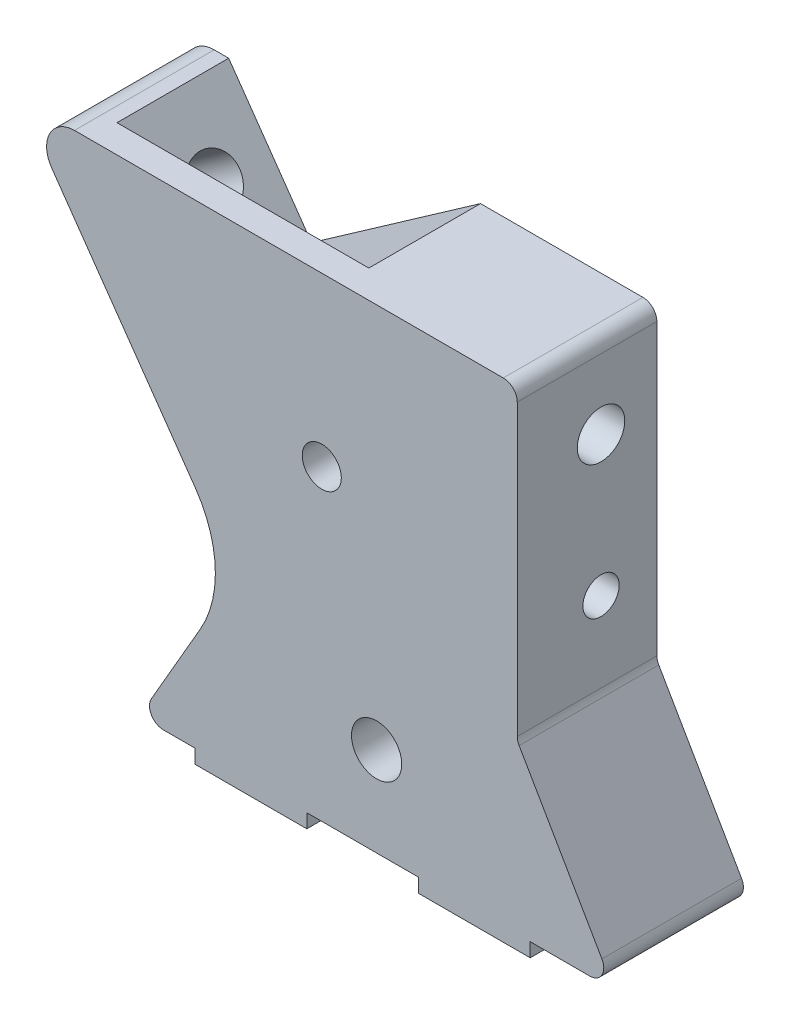
SolidWorks part; units mm, degrees
material "ABS"
ref_plane "Спереди" through (0, 0, 0) normal (0, 0, 1) x (1, 0, 0)
ref_plane "Сверху" through (0, 0, 0) normal (0, 1, 0) x (1, 0, 0)
ref_plane "Справа" through (0, 0, 0) normal (1, 0, 0) x (0, 0, -1)
sketch "Sketch1" plane through (0, 0, 0) normal (0, 0, 1) x (1, 0, 0)
  line L0 (0, 0) -> (85, 0)
  line L1 (85, 0) -> (67.6795, 30)
  line L2 (67.6795, 30) -> (67.6795, 85)
  line L3 (67.6795, 85) -> (-21.1909, 85)
  line L4 (-21.1909, 85) -> (10.0123, 40.4371)
  line L5 (10.9498, 18.9656) -> (0, 0)
  arc A0 (10.9498, 18.9656) -> (10.0123, 40.4371) centre (-6.3707, 28.9656) ccw
  point P9 (17.3205, 30)
  dimension "D1" = 85
  dimension "D7" = 20
  dimension "D2" = 60
  dimension "D3" = 30
  dimension "D4" = 55
  dimension "D5" = 55
  dimension "D6" = 60
extrude "Boss-Extrude1" add sketch "Sketch1" against normal blind 25
sketch "Sketch5" plane through (67.6795, 0, 0) normal (1, 0, 0) x (0, 0, -1)
  line L0 (0, 30) -> (0, 85) construction
  line L1 (25, 85) -> (0, 85) construction
  circle A0 centre (15, 45) radius 3.25
  circle A1 centre (15, 70) radius 4.25
  dimension "D1" = 6.5
  dimension "D2" = 8.5
  dimension "D3" = 15
  dimension "D4" = 15
  dimension "D5" = 15
  dimension "D6" = 40
extrude "Cut-Extrude2" cut sketch "Sketch5" against normal blind 15
sketch "Sketch6" plane through (25.7176, 18.0077, 0) normal (-0.8192, -0.5736, 0) x (0, 0, 1)
  line L0 (0, 81.7825) -> (0, 27.3813) construction
  line L1 (-25, 81.7825) -> (0, 81.7825) construction
  circle A0 centre (-15, 61.7825) radius 4.5
  dimension "D1" = 9
  dimension "D2" = 15
  dimension "D3" = 20
extrude "Cut-Extrude3" cut sketch "Sketch6" against normal through all
sketch "Sketch7" plane through (0, 0, -25) normal (0, 0, -1) x (-1, 0, 0)
  line L0 (-57.6795, 80) -> (-57.6795, 32.5)
  line L1 (-57.6795, 32.5) -> (-21.6739, 32.5)
  line L2 (-21.6739, 32.5) -> (-4.6219, 56.8528)
  line L3 (-37.6795, 80) -> (-57.6795, 80)
  line L4 (-63.3494, 27.5) -> (-76.3397, 5)
  line L5 (-76.3397, 5) -> (-8.6603, 5)
  line L6 (-8.6603, 5) -> (-21.6506, 27.5)
  line L7 (-21.6506, 27.5) -> (-63.3494, 27.5)
  line L8 (-85, 0) -> (-67.6795, 30) construction
  line L9 (0, 0) -> (-85, 0) construction
  line L10 (-10.9498, 18.9656) -> (0, 0) construction
  line L11 (21.1909, 85) -> (-10.0123, 40.4371) construction
  line L12 (-67.6795, 30) -> (-67.6795, 85) construction
  line L13 (-67.6795, 85) -> (21.1909, 85) construction
  line L14 (-37.6795, 80) -> (-4.6219, 56.8528)
  line L15 (-36.103, 85) -> (-5.8497, 63.8164)
  line L16 (-5.8497, 63.8164) -> (8.9832, 85)
  line L17 (-36.103, 85) -> (8.9832, 85)
  dimension "D1" = 10
  dimension "D2" = 5
  dimension "D3" = 5
  dimension "D4" = 5
  dimension "D5" = 5
  dimension "D6" = 5
  dimension "D7" = 5
  dimension "D8" = 47.5
  dimension "D9" = 5
  dimension "D10" = 10
  dimension "D11" = 20
extrude "Cut-Extrude4" cut sketch "Sketch7" against normal blind 20
sketch "Sketch8" plane through (0, 0, 0) normal (0, -1, 0) x (1, 0, 0)
  line L5 (0, -25) -> (85, -25) construction
  line L6 (70, -25) -> (50, -25)
  line L7 (70, -25) -> (70, 0)
  line L8 (70, 0) -> (50, 0)
  line L9 (50, -25) -> (50, 0)
  line L10 (0, 0) -> (85, 0) construction
  line L11 (85, -25) -> (85, 0) construction
  line L12 (30, -25) -> (10, -25)
  line L13 (30, -25) -> (30, 0)
  line L14 (30, 0) -> (10, 0)
  line L15 (10, -25) -> (10, 0)
  dimension "D1" = 20
  dimension "D2" = 20
  dimension "D3" = 15
extrude "Boss-Extrude2" add sketch "Sketch8" along normal blind 2.5
sketch "Sketch10" plane through (0, 0, -5) normal (0, 0, -1) x (-1, 0, 0)
  line L0 (-67.6795, 30) -> (-67.6795, 85) construction
  line L1 (-67.6795, 85) -> (21.1909, 85) construction
  line L2 (0, 0) -> (-10, 0) construction
  circle A0 centre (-32.6795, 55) radius 8.75
  circle A1 centre (-42.5, 16) radius 8.75
  dimension "D1" = 17.5
  dimension "D2" = 17.5
  dimension "D3" = 35
  dimension "D4" = 30
  dimension "D5" = 16
  dimension "D6" = 42.5
extrude "Boss-Extrude6" add sketch "Sketch10" along normal blind 5
sketch "Sketch3" plane through (0, 0, 0) normal (0, 0, 1) x (1, 0, 0)
  line L1 (67.6795, 30) -> (67.6795, 85) construction
  line L2 (67.6795, 85) -> (-21.1909, 85) construction
  line L3 (70, 0) -> (85, 0) construction
  circle A0 centre (32.6795, 55) radius 3.5
  circle A1 centre (42.5, 16) radius 4.5
  dimension "D1" = 7
  dimension "D2" = 9
  dimension "D3" = 16
  dimension "D4" = 42.5
  dimension "D5" = 35
  dimension "D6" = 30
extrude "Cut-Extrude5" cut sketch "Sketch3" against normal through all
fillet "Fillet1" radius 5 1 edges at (-21.1909, 85, -12.5)
fillet "Fillet2" radius 2.5 4 edges at (0, 0, -12.5) (67.6795, 30, -12.5) (85, 0, -12.5) (67.6795, 85, -12.5)
